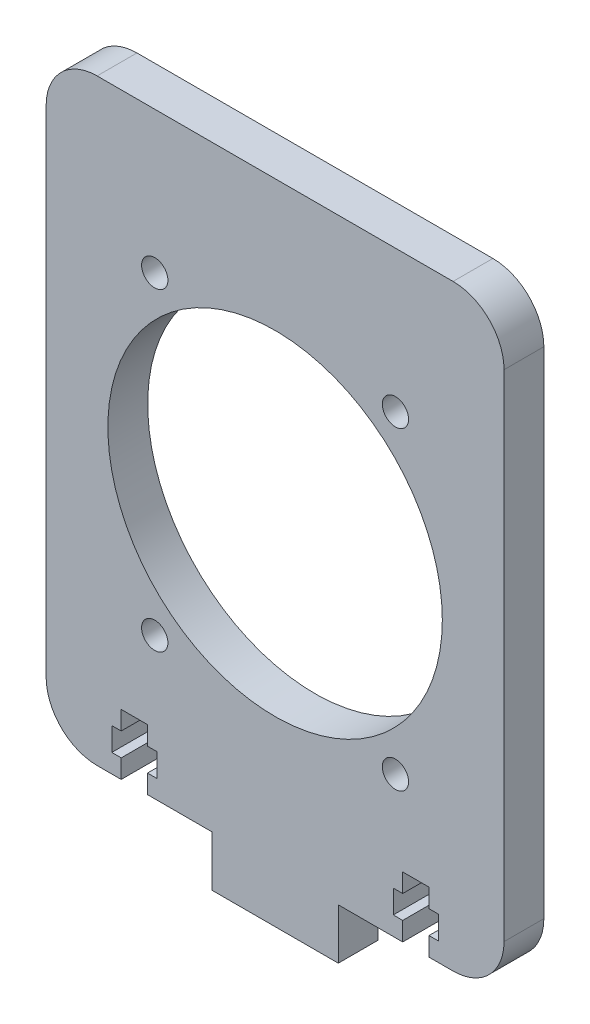
SolidWorks part; units mm, degrees
ref_plane "Front Plane" through (0, 0, 0) normal (0, 0, 1) x (1, 0, 0)
ref_plane "Top Plane" through (0, 0, 0) normal (0, 1, 0) x (1, 0, 0)
ref_plane "Right Plane" through (0, 0, 0) normal (1, 0, 0) x (0, 0, -1)
sketch "Sketch1" plane through (0, 0, 0) normal (0, 0, 1) x (1, 0, 0)
  line L0 (0, 0) -> (-30.2269, 39.4264)
  line L1 (-57.5, 75) -> (57.5, 75)
  line L2 (-57.5, 75) -> (-57.5, -75)
  line L3 (-57.5, -75) -> (57.5, -75)
  line L4 (57.5, 75) -> (57.5, -75)
  line L5 (-57.5, 75) -> (57.5, -75) construction
  line L6 (-57.5, -75) -> (57.5, 75) construction
  line L7 (-57.5, 0) -> (57.5, 0) construction
  line L8 (0, 75) -> (0, -75) construction
  circle A0 centre (0, 0) radius 42
  circle A1 centre (-30.2269, 39.4264) radius 3.3
  circle A2 centre (30.2269, 39.4264) radius 3.3
  circle A3 centre (30.2269, -39.4264) radius 3.3
  circle A4 centre (-30.2269, -39.4264) radius 3.3
  point P19 (0, 0)
  dimension "D1" = 84
  dimension "D5" = 6.6
  dimension "D2" = 115
  dimension "D3" = 150
  dimension "D4" = 49.68
extrude "Boss-Extrude1" add sketch "Sketch1" along normal blind 10
sketch "Sketch2" plane through (0, 0, 0) normal (0, 0, -1) x (-1, 0, 0)
  line L0 (0, -75) -> (32.05, -75)
  line L1 (57.5, -75) -> (-57.5, -75) construction
  line L2 (32.05, -75) -> (32.05, -70.3)
  line L3 (32.05, -70.3) -> (29.686, -70.3)
  line L4 (29.686, -70.3) -> (29.686, -64.46)
  line L5 (29.686, -64.46) -> (32.05, -64.46)
  line L6 (32.05, -64.46) -> (32.05, -59.76)
  line L7 (32.05, -59.76) -> (38.65, -59.76)
  line L8 (38.65, -59.76) -> (38.65, -64.46)
  line L9 (38.65, -64.46) -> (41.014, -64.46)
  line L10 (41.014, -64.46) -> (41.014, -70.3)
  line L11 (41.014, -70.3) -> (38.65, -70.3)
  line L12 (38.65, -70.3) -> (38.65, -75)
  line L13 (38.65, -75) -> (32.05, -75)
  line L14 (0, -75) -> (0, 0) construction
  line L15 (-38.65, -75) -> (-32.05, -75)
  line L16 (-38.65, -70.3) -> (-38.65, -75)
  line L17 (-41.014, -70.3) -> (-38.65, -70.3)
  line L18 (-41.014, -64.46) -> (-41.014, -70.3)
  line L19 (-38.65, -64.46) -> (-41.014, -64.46)
  line L20 (-38.65, -59.76) -> (-38.65, -64.46)
  line L21 (-32.05, -59.76) -> (-38.65, -59.76)
  line L22 (-32.05, -64.46) -> (-32.05, -59.76)
  line L23 (-29.686, -64.46) -> (-32.05, -64.46)
  line L24 (-29.686, -70.3) -> (-29.686, -64.46)
  line L25 (-32.05, -70.3) -> (-29.686, -70.3)
  line L26 (-32.05, -75) -> (-32.05, -70.3)
  line M18 (-57.5, -75) -> (57.5, -75)
  dimension "D1" = 32.05
  dimension "D2" = 5.84
  dimension "D3" = 6.6
  dimension "D4" = 15.24
  dimension "D5" = 11.328
extrude "Cut-Extrude1" cut sketch "Sketch2" against normal through all contours L26 L25 L24 L23 L22 L21 L20 L19 L18 L17 L16 M18 | L2 L3 L4 L5 L6 L7 L8 L9 L10 L11 L12 L13
sketch "Sketch4" plane through (0, -75, 0) normal (0, -1, 0) x (1, 0, 0)
  line L0 (0, 0) -> (15.875, 0)
  line L1 (-32.05, 0) -> (32.05, 0) construction
  line L2 (15.875, 0) -> (15.875, 10)
  line L3 (-32.05, 10) -> (32.05, 10) construction
  line L4 (15.875, 10) -> (-15.875, 10)
  line L5 (-15.875, 10) -> (-15.875, 0)
  line L6 (-15.875, 0) -> (0, 0)
  dimension "D1" = 31.75
extrude "Boss-Extrude2" add sketch "Sketch4" along normal blind 12.7
fillet "Fillet1" radius 12.8 4 edges at (-57.5, 75, 5) (-57.5, -75, 5) (57.5, -75, 5) (57.5, 75, 5)
